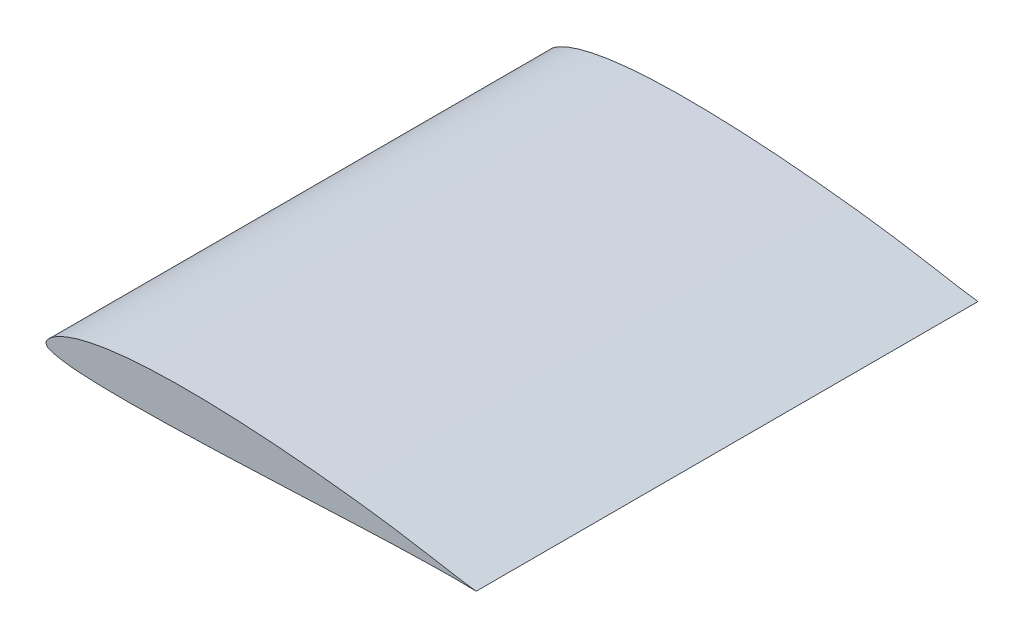
SolidWorks part; units mm, degrees
ref_plane "Front Plane" through (0, 0, 0) normal (0, 0, 1) x (1, 0, 0)
ref_plane "Top Plane" through (0, 0, 0) normal (0, 1, 0) x (1, 0, 0)
ref_plane "Right Plane" through (0, 0, 0) normal (1, 0, 0) x (0, 0, -1)
curve "Curve1"
  spline degree 3 poles (152.4, 0, 0) (152.2328, 0.0185, 0) (151.5718, 0.0917, 0) (150.114, 0.2839, 0) (147.7494, 0.6387, 0) (144.5559, 1.1702, 0) (140.6154, 1.8591, 0) (136.0078, 2.6715, 0) (130.8064, 3.5628, 0) (125.0738, 4.4862, 0) (118.8647, 5.3978, 0) (112.2333, 6.273, 0) (105.2435, 7.1061, 0) (97.9697, 7.8893, 0) (90.4927, 8.6067, 0) (82.8953, 9.2407, 0) (75.2587, 9.7775, 0) (67.6629, 10.1988, 0) (60.1868, 10.4917, 0) (52.9059, 10.6451, 0) (45.8917, 10.6446, 0) (39.2107, 10.4862, 0) (32.9233, 10.1644, 0) (27.0837, 9.6709, 0) (21.7372, 9.0165, 0) (16.9243, 8.2041, 0) (12.6763, 7.2498, 0) (9.0198, 6.1745, 0) (5.9657, 5.002, 0) (3.544, 3.7699, 0) (1.7048, 2.5315, 0) (0.5752, 1.3447, 0) (-0.1707, 0.2031, 0) (0.3376, -1.0018, 0) (1.7929, -1.5467, 0) (3.7942, -2.1772, 0) (6.6434, -2.6439, 0) (10.2161, -3.042, 0) (14.5301, -3.3199, 0) (19.534, -3.4977, 0) (25.1869, -3.5776, 0) (31.4286, -3.5738, 0) (38.1919, -3.4966, 0) (45.4016, -3.3493, 0) (52.9784, -3.1418, 0) (60.8387, -2.8853, 0) (68.895, -2.5879, 0) (77.0574, -2.2589, 0) (85.235, -1.9077, 0) (93.3354, -1.5502, 0) (101.266, -1.1955, 0) (108.9342, -0.8624, 0) (116.2465, -0.5575, 0) (123.1102, -0.3069, 0) (129.4317, -0.1079, 0) (135.1235, 0.028, 0) (140.1036, 0.1089, 0) (144.2994, 0.1399, 0) (147.6448, 0.1242, 0) (150.0834, 0.0865, 0) (151.3998, 0.0403, 0) (151.8986, 0.0229, 0) knots 0 0 0 0 0.001635 0.006466 0.014297 0.024884 0.037944 0.053194 0.070377 0.089257 0.109652 0.131396 0.154295 0.178097 0.202531 0.227329 0.252226 0.276966 0.301297 0.324972 0.347773 0.369494 0.389947 0.408979 0.426466 0.442307 0.456421 0.468774 0.479345 0.488156 0.495223 0.500608 0.504417 0.507344 0.511893 0.518766 0.528062 0.53975 0.553782 0.570059 0.588441 0.608748 0.63075 0.654208 0.678865 0.704451 0.730678 0.757254 0.783883 0.810266 0.836095 0.861073 0.884897 0.907258 0.927856 0.946395 0.962618 0.976286 0.987193 0.995147 1 1 1 1
sketch "Sketch1" plane through (0, 0, 0) normal (0, 0, 1) x (1, 0, 0)
  spline S0 degree 3 poles (-120.0863, -2986.5223) (204.7313, 14.3063) (176.6016, -3.2082) (150.114, 0.2839) (147.7494, 0.6387) (144.5559, 1.1702) (140.6154, 1.8591) (136.0078, 2.6715) (130.8064, 3.5628) (125.0738, 4.4862) (118.8647, 5.3978) (112.2333, 6.273) (105.2435, 7.1061) (97.9697, 7.8893) (90.4927, 8.6067) (82.8953, 9.2407) (75.2587, 9.7775) (67.6629, 10.1988) (60.1868, 10.4917) (52.9059, 10.6451) (45.8917, 10.6446) (39.2107, 10.4862) (32.9233, 10.1644) (27.0837, 9.6709) (21.7372, 9.0165) (16.9243, 8.2041) (12.6763, 7.2498) (9.0198, 6.1745) (5.9657, 5.002) (3.544, 3.7699) (1.7048, 2.5315) (0.5752, 1.3447) (-0.1707, 0.2031) (0.3376, -1.0018) (1.7929, -1.5467) (3.7942, -2.1772) (6.6434, -2.6439) (10.2161, -3.042) (14.5301, -3.3199) (19.534, -3.4977) (25.1869, -3.5776) (31.4286, -3.5738) (38.1919, -3.4966) (45.4016, -3.3493) (52.9784, -3.1418) (60.8387, -2.8853) (68.895, -2.5879) (77.0574, -2.2589) (85.235, -1.9077) (93.3354, -1.5502) (101.266, -1.1955) (108.9342, -0.8624) (116.2465, -0.5575) (123.1102, -0.3069) (129.4317, -0.1079) (135.1235, 0.028) (140.1036, 0.1089) (144.2994, 0.1399) (147.6448, 0.1242) (196.5916, -0.6332) (243.4783, -35.3543) (374.0575, 2989.6631) knots -0.245458 -0.245458 -0.245458 -0.245458 0.001635 0.006466 0.014297 0.024884 0.037944 0.053194 0.070377 0.089257 0.109652 0.131396 0.154295 0.178097 0.202531 0.227329 0.252226 0.276966 0.301297 0.324972 0.347773 0.369494 0.389947 0.408979 0.426466 0.442307 0.456421 0.468774 0.479345 0.488156 0.495223 0.500608 0.504417 0.507344 0.511893 0.518766 0.528062 0.53975 0.553782 0.570059 0.588441 0.608748 0.63075 0.654208 0.678865 0.704451 0.730678 0.757254 0.783883 0.810266 0.836095 0.861073 0.884897 0.907258 0.927856 0.946395 0.962618 0.976286 0.987193 0.995147 1.45225 1.45225 1.45225 1.45225 only from (152.4, 0) to (151.8986, 0.0229) construction
  spline S1 degree 3 poles (152.4, 0) (152.2328, 0.0185) (151.5718, 0.0917) (150.114, 0.2839) (147.7494, 0.6387) (144.5559, 1.1702) (140.6154, 1.8591) (136.0078, 2.6715) (130.8064, 3.5628) (125.0738, 4.4862) (118.8647, 5.3978) (112.2333, 6.273) (105.2435, 7.1061) (97.9697, 7.8893) (90.4927, 8.6067) (82.8953, 9.2407) (75.2587, 9.7775) (67.6629, 10.1988) (60.1868, 10.4917) (52.9059, 10.6451) (45.8917, 10.6446) (39.2107, 10.4862) (32.9233, 10.1644) (27.0837, 9.6709) (21.7372, 9.0165) (16.9243, 8.2041) (12.6763, 7.2498) (9.0198, 6.1745) (5.9657, 5.002) (3.544, 3.7699) (1.7048, 2.5315) (0.5752, 1.3447) (-0.1707, 0.2031) (0.3376, -1.0018) (1.7929, -1.5467) (3.7942, -2.1772) (6.6434, -2.6439) (10.2161, -3.042) (14.5301, -3.3199) (19.534, -3.4977) (25.1869, -3.5776) (31.4286, -3.5738) (38.1919, -3.4966) (45.4016, -3.3493) (52.9784, -3.1418) (60.8387, -2.8853) (68.895, -2.5879) (77.0574, -2.2589) (85.235, -1.9077) (93.3354, -1.5502) (101.266, -1.1955) (108.9342, -0.8624) (116.2465, -0.5575) (123.1102, -0.3069) (129.4317, -0.1079) (135.1235, 0.028) (140.1036, 0.1089) (144.2994, 0.1399) (147.6448, 0.1242) (150.0834, 0.0865) (151.3998, 0.0403) (151.8986, 0.0229) knots 0 0 0 0 0.001635 0.006466 0.014297 0.024884 0.037944 0.053194 0.070377 0.089257 0.109652 0.131396 0.154295 0.178097 0.202531 0.227329 0.252226 0.276966 0.301297 0.324972 0.347773 0.369494 0.389947 0.408979 0.426466 0.442307 0.456421 0.468774 0.479345 0.488156 0.495223 0.500608 0.504417 0.507344 0.511893 0.518766 0.528062 0.53975 0.553782 0.570059 0.588441 0.608748 0.63075 0.654208 0.678865 0.704451 0.730678 0.757254 0.783883 0.810266 0.836095 0.861073 0.884897 0.907258 0.927856 0.946395 0.962618 0.976286 0.987193 0.995147 1 1 1 1
  spline S2 degree 1 poles (151.8986, 0.0229) (152.4, 0) knots 0 0 1 1
extrude "Boss-Extrude1" add sketch "Sketch1" along normal blind 177.8
